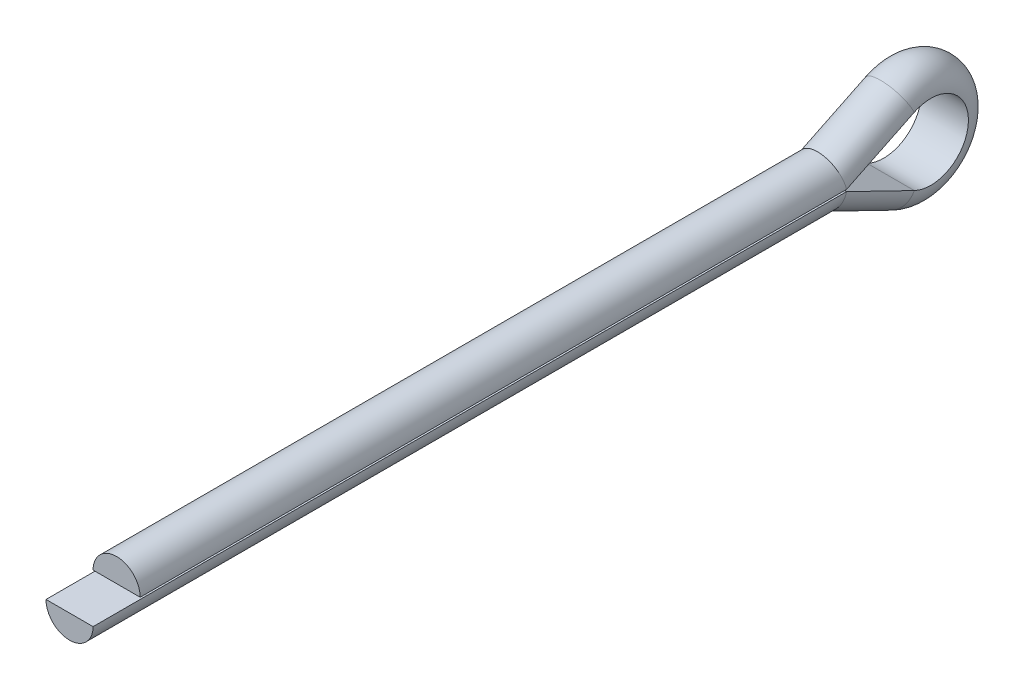
SolidWorks part; units mm, degrees
ref_plane "Front" through (0, 0, 0) normal (0, 0, 1) x (1, 0, 0)
ref_plane "Top" through (0, 0, 0) normal (0, 1, 0) x (1, 0, 0)
ref_plane "Right" through (0, 0, 0) normal (1, 0, 0) x (0, 0, -1)
ref_plane "Plane1" through (0, 0, -3.175) normal (0, 0, 1) x (1, 0, 0)
sketch "Sketch2" plane through (0, 0, 0) normal (1, 0, 0) x (0, 0, -1)
  line L0 (50.8, 0) -> (3.175, 0)
  line L1 (50.8, 0) -> (55.3688, 2.2209)
  line L2 (50.8, -0.127) -> (55.3688, -2.3479)
  line L3 (50.8, -0.127) -> (0, -0.127)
  arc A0 (55.3688, -2.3479) -> (55.3688, 2.2209) centre (56.4793, -0.0635) ccw
  dimension "D1" = 5.08
  dimension "D5" = 5.08
  dimension "D6" = 0.0635
  dimension "D4" = 3.175
  dimension "D2" = 50.8
  dimension "D3" = 0.127
sketch "Sketch3" plane through (0, 0, -3.175) normal (0, 0, 1) x (1, 0, 0)
  line L0 (-1.5875, 0) -> (1.5875, 0)
  arc A0 (-1.5875, 0) -> (1.5875, 0) centre (0, 0) cw
  point P3 (0, 0)
  dimension "D1" = 3.175
sweep "Sweep2" add profiles "Sketch3" path "Sketch2"
